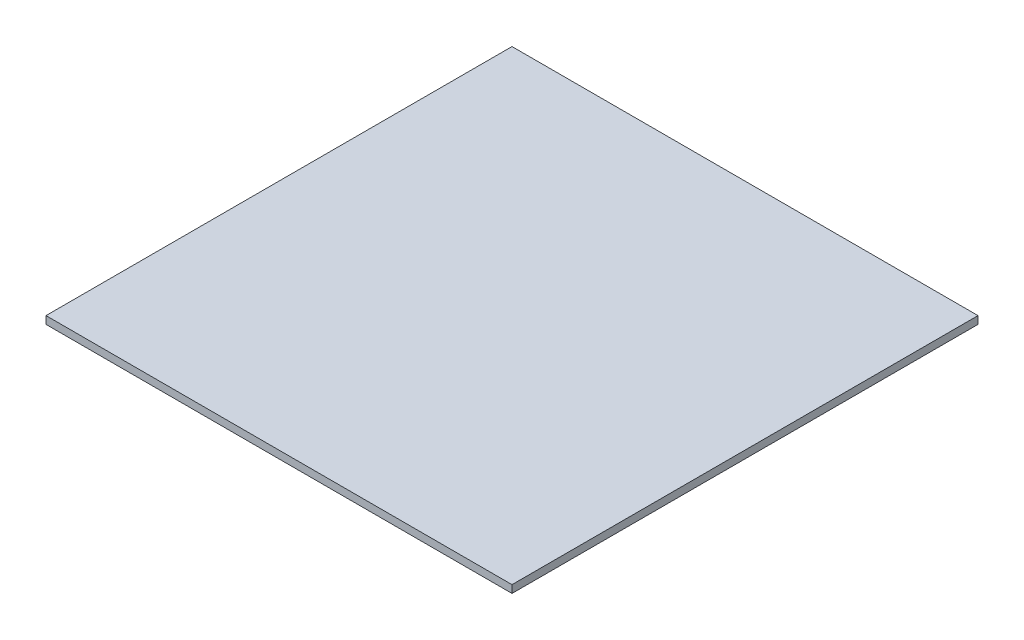
SolidWorks part; units mm, degrees
ref_plane "Front Plane" through (0, 0, 0) normal (0, 0, 1) x (1, 0, 0)
ref_plane "Top Plane" through (0, 0, 0) normal (0, 1, 0) x (1, 0, 0)
ref_plane "Right Plane" through (0, 0, 0) normal (1, 0, 0) x (0, 0, -1)
sketch "Sketch1" plane through (0, 0, 0) normal (0, 1, 0) x (1, 0, 0)
  line L1 (-610, 610) -> (610, 610)
  line L2 (-610, 610) -> (-610, -610)
  line L3 (-610, -610) -> (610, -610)
  line L4 (610, 610) -> (610, -610)
  line L5 (-610, 610) -> (610, -610) construction
  line L6 (-610, -610) -> (610, 610) construction
  point P0 (0, 0)
  dimension "D1" = 1220
  dimension "D2" = 1220
extrude "Boss-Extrude1" add sketch "Sketch1" along normal blind 20
